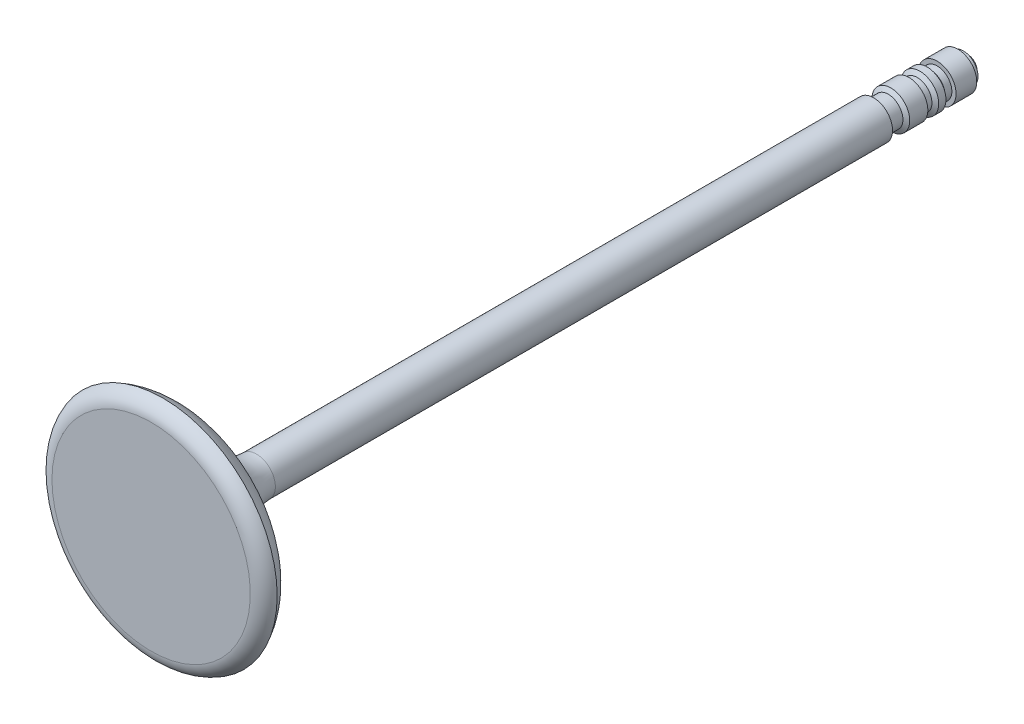
SolidWorks part; units mm, degrees
ref_plane "Front Plane" through (0, 0, 0) normal (0, 0, 1) x (1, 0, 0)
ref_plane "Top Plane" through (0, 0, 0) normal (0, 1, 0) x (1, 0, 0)
ref_plane "Right Plane" through (0, 0, 0) normal (1, 0, 0) x (0, 0, -1)
sketch "Sketch1" plane through (0, 0, 0) normal (1, 0, 0) x (0, 0, -1)
  line L0 (-120.5185, 0) -> (143.6059, 0) construction
  line L1 (9.226, 92.2984) -> (307.2474, 92.2984) construction
  line L2 (0, 80.0285) -> (0, -100.2651) construction
  line L3 (55.5535, 0) -> (-41.6927, 0)
  line L4 (-41.6927, 0) -> (-41.6927, 11.8145)
  line L5 (-29.14, 2.25) -> (44.3826, 2.25)
  line L6 (44.3826, 2.25) -> (44.3826, 1.7525)
  line L7 (44.3826, 1.7525) -> (46.119, 1.7525)
  line L8 (46.119, 1.7525) -> (46.4274, 2.25)
  line L9 (46.4274, 2.25) -> (48.5866, 2.25)
  line L10 (48.5866, 2.25) -> (48.5866, 1.7525)
  line L11 (48.5866, 1.7525) -> (49.5737, 1.7525)
  line L12 (49.5737, 1.7525) -> (49.8822, 2.25)
  line L13 (49.8822, 2.25) -> (50.7459, 2.25)
  line L14 (50.7459, 2.25) -> (50.7459, 2.0012)
  line L15 (50.7459, 2.0012) -> (51.1471, 1.7525)
  line L16 (51.1471, 1.7525) -> (51.9489, 1.7525)
  line L17 (51.9489, 1.7525) -> (51.9489, 2.25)
  line L18 (51.9489, 2.25) -> (54.4165, 2.25)
  line L19 (54.4165, 2.25) -> (54.4165, 1.7525)
  line L20 (54.4165, 1.7525) -> (55.0643, 1.7525)
  line L21 (55.0643, 1.7525) -> (55.0643, 1.1664)
  line L22 (55.0643, 1.1664) -> (55.5535, 1.1664)
  line L23 (55.5535, 1.1664) -> (55.5535, 0)
  arc A0 (-41.6927, 11.8145) -> (-40.2755, 13.6) centre (-39.7151, 11.7) cw
  arc A1 (-40.2755, 13.6) -> (-37.1473, 9.7018) centre (-42.939, 8.2584) cw
  arc A2 (-37.1473, 9.7018) -> (-32.8161, 3.4909) centre (-25.9373, 12.9037) ccw
  arc A3 (-32.8161, 3.4909) -> (-29.14, 2.25) centre (-29.2827, 7.8925) ccw
  dimension "D1" = 13.6
  dimension "D2" = 2.25
revolve "Revolve1" add sketch "Sketch1" angle 360 about L3
